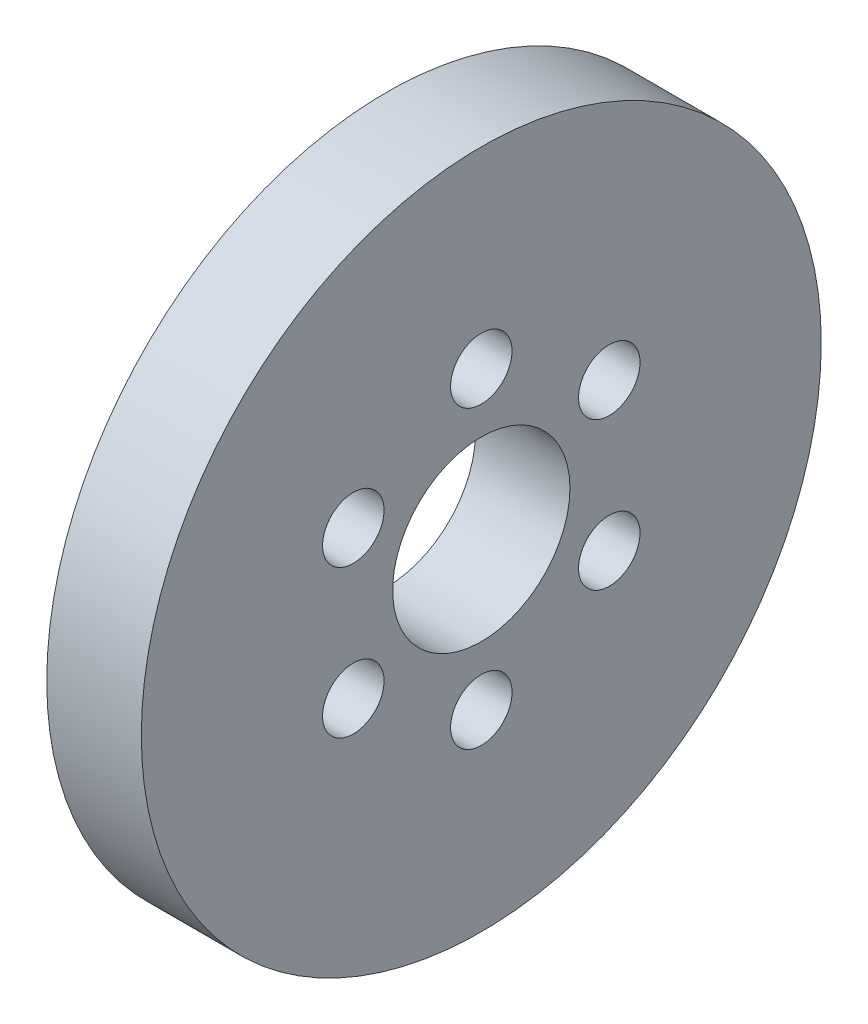
SolidWorks part; units mm, degrees
ref_plane "Front Plane" through (0, 0, 0) normal (0, 0, 1) x (1, 0, 0)
ref_plane "Top Plane" through (0, 0, 0) normal (0, 1, 0) x (1, 0, 0)
ref_plane "Right Plane" through (0, 0, 0) normal (1, 0, 0) x (0, 0, -1)
sketch "Sketch1" plane through (0, 0, 0) normal (1, 0, 0) x (0, 0, -1)
  circle A0 centre (0, 0) radius 18.2601
  dimension "D1" = 36.5201
extrude "Boss-Extrude1" add sketch "Sketch1" along normal blind 5.08
hole_wizard "#4 Clearance Hole1" positions "Sketch3" profile "Sketch2" hole size "#4" standard "Progressive" end condition through all
sketch "Sketch3" plane through (5.08, 0, 0) normal (1, 0, 0) x (0, 0, -1)
  line L0 (0, 0) -> (0, 7.9375) construction
  line L1 (0, 0) -> (6.8741, 3.9687) construction
  line L2 (0, 0) -> (6.8741, -3.9688) construction
  line L3 (0, 0) -> (0, -7.9375) construction
  line L4 (0, 0) -> (-6.8741, -3.9687) construction
  line L5 (0, 0) -> (-6.8741, 3.9688) construction
  point P5 (0, 7.9375)
  point P16 (6.8741, 3.9687)
  point P17 (6.8741, -3.9688)
  point P18 (0, -7.9375)
  point P19 (-6.8741, -3.9687)
  point P20 (-6.8741, 3.9688)
  point P21 (0, 0)
  dimension "D1" = 7.9375
  dimension "D2" = 6
sketch "Sketch2" plane through (5.08, 7.9375, 0) normal (0, 1, 0) x (0, 0, -1)
  line L0 (0, 0) -> (0, 5.08)
  line L1 (0, 5.08) -> (1.651, 5.08)
  line L2 (1.651, 5.08) -> (1.651, 0)
  line L5 (1.651, 0) -> (0, 0)
  line L11 (0, -6.35) -> (0, 107.95) construction
  dimension "Thru Hole Dia." = 3.302
  dimension "Thru Hole Depth" = 5.08
hole_wizard "#4 Clearance Hole2" positions "Sketch5" profile "Sketch4" hole size "#4" standard "Progressive"
sketch "Sketch5" plane through (5.08, 0, 0) normal (1, 0, 0) x (0, 0, -1)
  point P0 (0, 0)
sketch "Sketch4" plane through (5.08, 0, 0) normal (0, 1, 0) x (0, 0, -1)
  line L0 (0, 0) -> (0, 60.0116)
  line L1 (0, 60.0116) -> (4.7625, 57.15)
  line L2 (4.7625, 57.15) -> (4.7625, 0)
  line L5 (4.7625, 0) -> (0, 0)
  line L10 (0, 60.0116) -> (-4.7625, 57.15) construction
  line L11 (0, -6.35) -> (0, 107.95) construction
  dimension "Hole Dia." = 9.525
  dimension "Hole Depth" = 57.15
  dimension "Drill Angle" = 118
